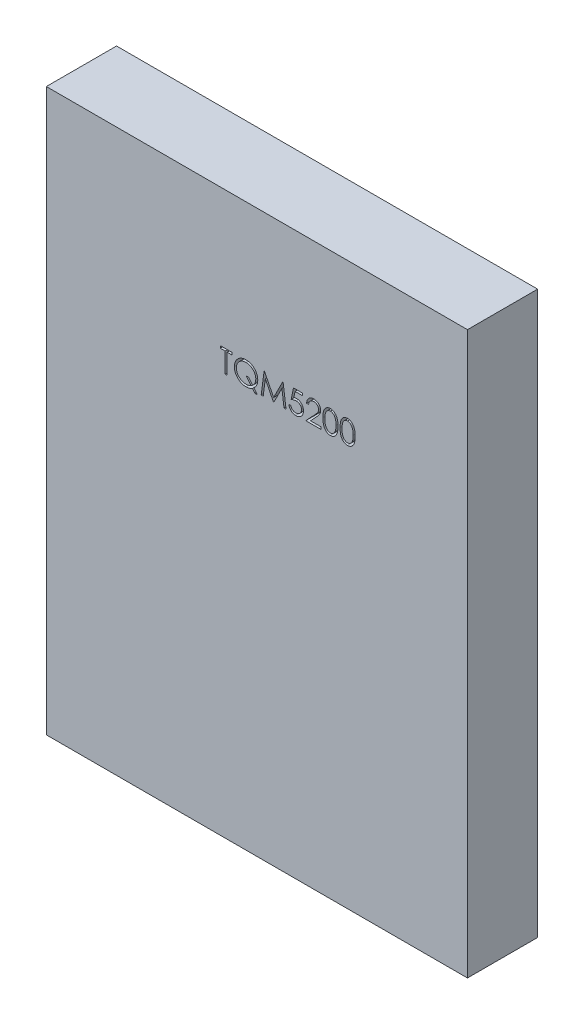
SolidWorks part; units mm, degrees
ref_plane "Front Plane" through (0, 0, 0) normal (0, 0, 1) x (1, 0, 0)
ref_plane "Top Plane" through (0, 0, 0) normal (0, 1, 0) x (1, 0, 0)
ref_plane "Right Plane" through (0, 0, 0) normal (1, 0, 0) x (0, 0, -1)
sketch "Sketch1" plane through (0, 0, 0) normal (0, 0, 1) x (1, 0, 0)
  line L1 (-30, -40) -> (30, -40)
  line L2 (-30, -40) -> (-30, 40)
  line L3 (-30, 40) -> (30, 40)
  line L4 (30, -40) -> (30, 40)
  line L5 (-30, -40) -> (30, 40) construction
  line L6 (-30, 40) -> (30, -40) construction
  point P0 (0, 0)
  dimension "D1" = 60
  dimension "D2" = 80
extrude "Extrude1" add sketch "Sketch1" along normal blind 10
sketch "Sketch2" plane through (0, 0, 10) normal (0, 0, 1) x (1, 0, 0)
  text T0 "TQM5200"
extrude "Extrude2" cut sketch "Sketch2" against normal through all
